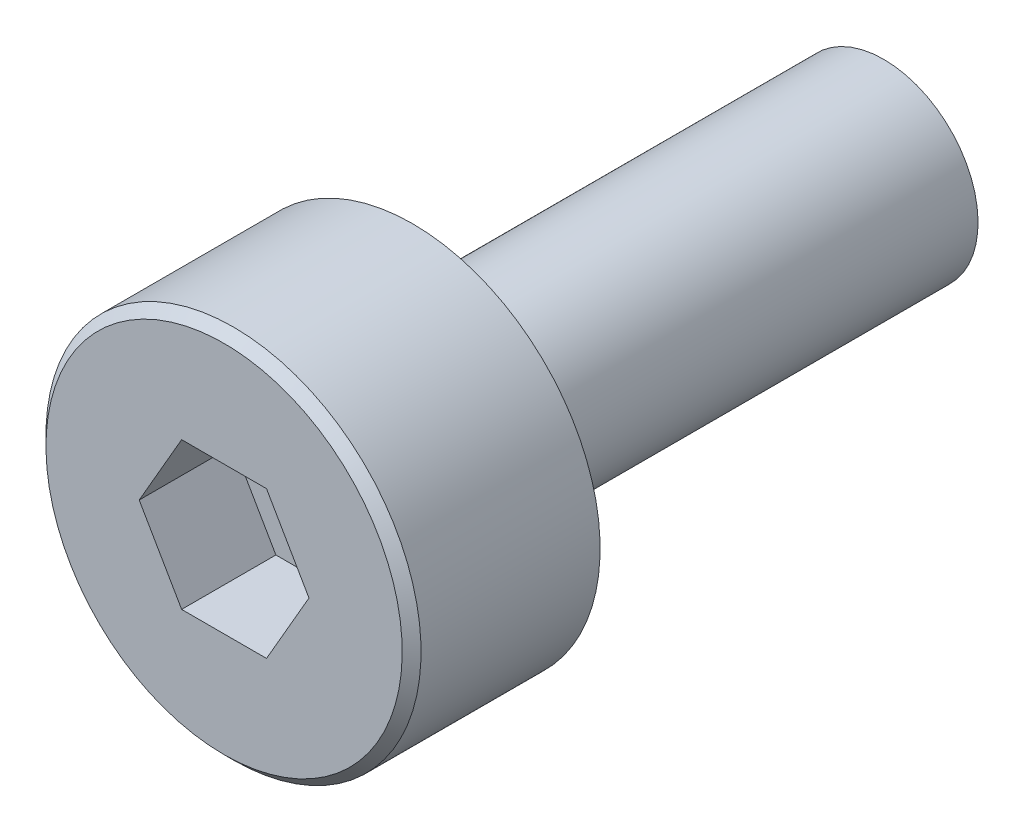
SolidWorks part; units mm, degrees
material "普通碳钢"
ref_plane "前视基准面" through (0, 0, 0) normal (0, 0, 1) x (1, 0, 0)
ref_plane "上视基准面" through (0, 0, 0) normal (0, 1, 0) x (1, 0, 0)
ref_plane "右视基准面" through (0, 0, 0) normal (1, 0, 0) x (0, 0, -1)
sketch "草图1" plane through (0, 0, 0) normal (1, 0, 0) x (0, 0, -1)
  line L0 (0, 0) -> (0, 1.99)
  line L1 (0, 1.99) -> (2, 1.99)
  line L2 (2, 1.99) -> (2, 1)
  line L3 (2, 1) -> (7, 1)
  line L4 (7, 1) -> (7, 0)
  line L5 (7, 0) -> (0, 0) construction
  line L6 (0, 0) -> (7, 0)
  dimension "D1" = 3.98
  dimension "D2" = 2
  dimension "D3" = 2
  dimension "D4" = 5
revolve "旋转1" add sketch "草图1" angle 360 about L5
cosmetic thread "装饰螺纹线1" parameters "D2"=1.567
sketch "草图2" plane through (0, 0, 0) normal (0, 0, 1) x (1, 0, 0)
  line L1 (0.4503, 0.78) -> (-0.4503, 0.78)
  line L2 (-0.4503, 0.78) -> (-0.9007, 0)
  line L3 (-0.9007, 0) -> (-0.4503, -0.78)
  line L4 (-0.4503, -0.78) -> (0.4503, -0.78)
  line L5 (0.4503, -0.78) -> (0.9007, 0)
  line L6 (0.9007, 0) -> (0.4503, 0.78)
  circle A0 centre (0, 0) radius 0.78 construction
  dimension "D1" = 1.56
extrude "切除-拉伸1" cut sketch "草图2" against normal blind 1
chamfer "装饰倒角" distance 0.1 angle 45 1 edges at (0, 1.99, 0)
